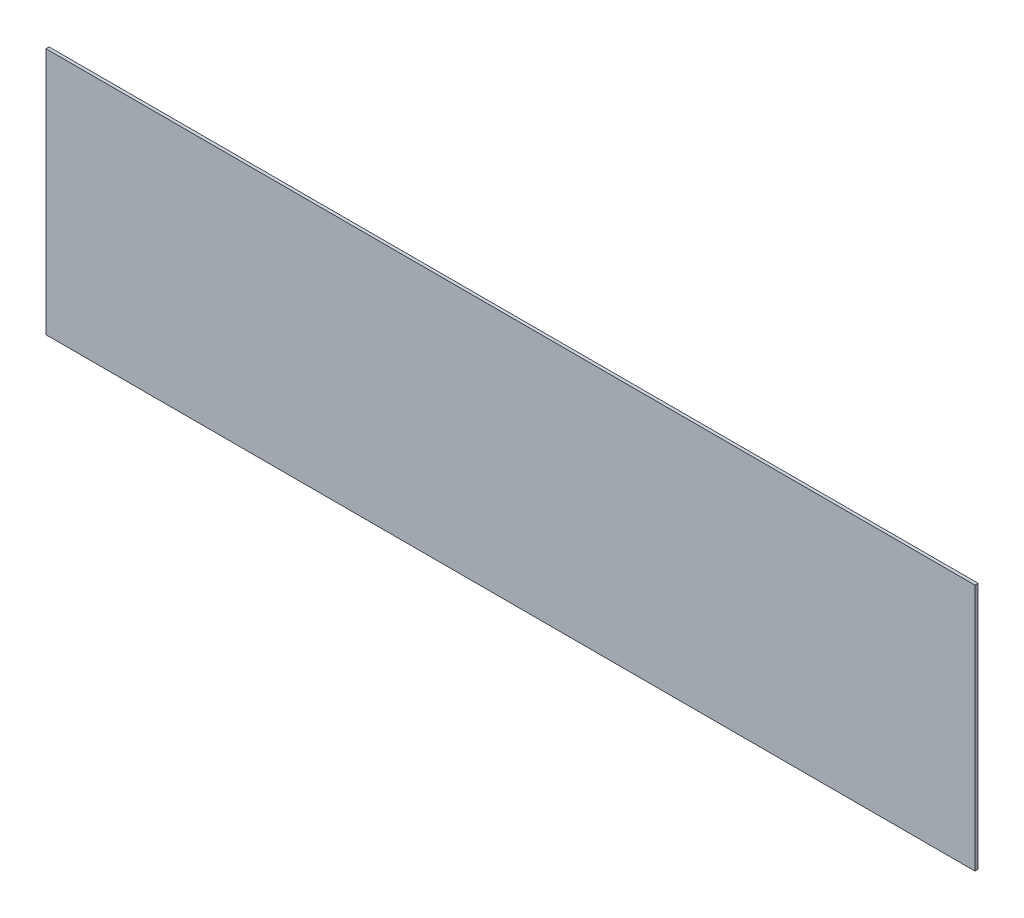
SolidWorks part; units mm, degrees
ref_plane "Front Plane" through (0, 0, 0) normal (0, 0, 1) x (1, 0, 0)
ref_plane "Top Plane" through (0, 0, 0) normal (0, 1, 0) x (1, 0, 0)
ref_plane "Right Plane" through (0, 0, 0) normal (1, 0, 0) x (0, 0, -1)
other "Configuration Table"
sketch "Sketch1" plane through (0, 0, 0) normal (0, 0, 1) x (1, 0, 0)
  line L1 (50, 130) -> (650, 130)
  line L2 (50, 130) -> (50, 290)
  line L3 (50, 290) -> (650, 290)
  line L4 (650, 130) -> (650, 290)
extrude "PACK_pano_plakasi_1" add sketch "Sketch1" against normal blind 2 from offset 248 separate body
